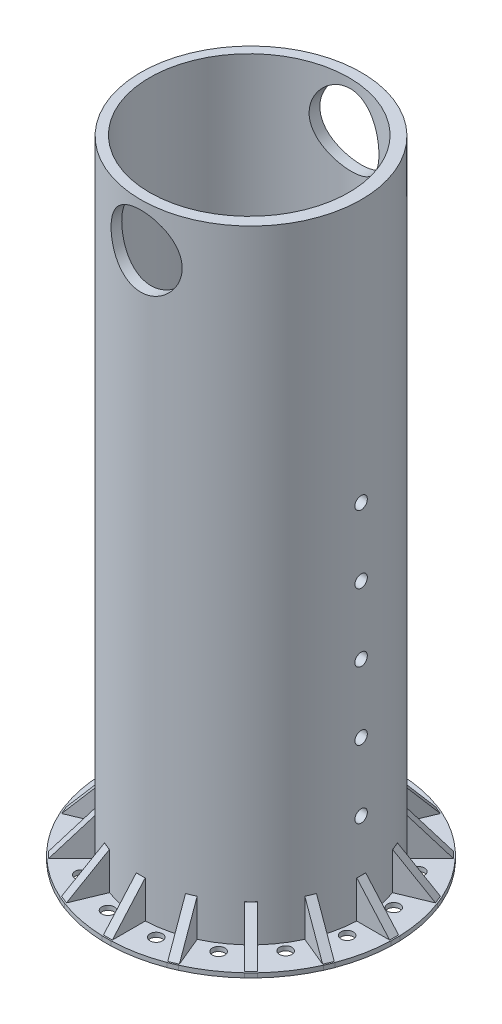
SolidWorks part; units mm, degrees
material "1023 Carbon Steel Sheet (SS)"
ref_plane "Front Plane" through (0, 0, 0) normal (0, 0, 1) x (1, 0, 0)
ref_plane "Top Plane" through (0, 0, 0) normal (0, 1, 0) x (1, 0, 0)
ref_plane "Right Plane" through (0, 0, 0) normal (1, 0, 0) x (0, 0, -1)
sketch "Sketch1" plane through (0, 0, 0) normal (0, 1, 0) x (1, 0, 0)
  circle A0 centre (0, 0) radius 162.5
  circle A1 centre (-1.9634, 0) radius 112
  dimension "D1" = 325
  dimension "D2" = 224
extrude "Boss-Extrude1" add sketch "Sketch1" along normal blind 5
sketch "Sketch2" plane through (0, 5, 0) normal (0, 1, 0) x (1, 0, 0)
  circle A0 centre (0, 0) radius 124
  circle A1 centre (-1.9634, 0) radius 112 construction
  circle A2 centre (-1.9634, 0) radius 112
  dimension "D1" = 248
extrude "Boss-Extrude2" add sketch "Sketch2" along normal blind 42
sketch "Sketch9" plane through (0, 47, 0) normal (0, 1, 0) x (1, 0, 0)
  line L1 (-119, 5) -> (-124, 5)
  line L2 (-119, 5) -> (-119, -5)
  line L3 (-119, -5) -> (-124, -5)
  line L4 (-124, 5) -> (-124, -5)
  circle A0 centre (0, 0) radius 124 construction
  circle A1 centre (0, 0) radius 124
  point P7 (-124, 0)
  circle M6 centre (0, 0) radius 124
  dimension "D1" = 10
  dimension "D2" = 5
extrude "Boss-Extrude7" add sketch "Sketch9" against normal blind 42 contours L3 L2 L1 M6
sketch "Sketch10" plane through (0, 0, 0) normal (0, 0, 1) x (1, 0, 0)
  line L0 (-124, 47) -> (-160.924, 5)
  line L1 (162.5, 5) -> (-162.5, 5) construction
  line L2 (-160.924, 5) -> (-124, 5)
  line L4 (-124, 5) -> (-124, 47)
sketch "Sketch11" plane through (0, 5, 0) normal (0, 1, 0) x (1, 0, 0)
  line L0 (-123.8992, -5) -> (-124, -5) construction
  line L1 (-124, 5) -> (-162.5, 5)
  line L2 (-124, 5) -> (-124, -5)
  line L3 (-124, -5) -> (-162.5, -5)
  line L4 (-162.5, 5) -> (-162.5, -5)
  circle A0 centre (0, 0) radius 162.5 construction
  circle A1 centre (0, 0) radius 162.5
  circle A3 centre (0, 0) radius 124 construction
  circle A4 centre (0, 0) radius 124
  point P8 (-162.5, 0)
  circle M6 centre (0, 0) radius 162.5
extrude "Boss-Extrude8" add sketch "Sketch11" against normal up to surface (5 mm away) contours L1 L4 M6 | L4 L3 L2 L1 M6
extrude "Boss-Extrude12" add sketch "Sketch10" along normal mid plane 10
pattern_circular "CirPattern1" count 16 over 360 about axis through (0, 0, 0) along (0, 1, 0) of "Boss-Extrude12", "Boss-Extrude8", "Boss-Extrude7"
sketch "Sketch13" plane through (0, 5, 0) normal (0, 1, 0) x (1, 0, 0)
  circle A0 centre (112.9258, -73.9781) radius 7
  circle A1 centre (0, 0) radius 135 construction
  dimension "D1" = 14
  dimension "D2" = 270
extrude "Cut-Extrude1" cut sketch "Sketch13" against normal through all
pattern_circular "CirPattern2" count 16 over 360 about axis through (-1.9634, 0, 0) along (0, 1, 0) of "Cut-Extrude1"
sketch "Sketch14" plane through (0, 47, 0) normal (0, 1, 0) x (1, 0, 0)
  circle A0 centre (0, 0) radius 124
  circle A2 centre (-1.9634, 0) radius 112 construction
  circle A3 centre (-1.9634, 0) radius 112
  dimension "D1" = 248
extrude "Boss-Extrude13" add sketch "Sketch14" along normal blind 658 contours A3 | A0
sketch "Sketch15" plane through (0, 0, 0) normal (0, 0, 1) x (1, 0, 0)
  line L0 (124, 705) -> (-124, 705) construction
  circle A0 centre (0, 655) radius 40
  dimension "D1" = 80
  dimension "D2" = 50
extrude "Cut-Extrude2" cut sketch "Sketch15" against normal through all both and the other way through all
sketch "Sketch16" plane through (0, 0, 0) normal (1, 0, 0) x (0, 0, -1)
  line L0 (42.7948, 5) -> (5, 5) construction
  line L1 (0, 705) -> (0, 0) construction
  line L2 (0, 0) -> (0, 253.6894) construction
  circle A0 centre (0, 105) radius 7
  circle A1 centre (0, 181.25) radius 7
  circle A2 centre (0, 257.5) radius 7
  circle A3 centre (0, 333.75) radius 7
  circle A4 centre (0, 410) radius 7
  point P4 (0, 337.4059)
  dimension "D1" = 14
  dimension "D2" = 100
  dimension "D4" = 305
  dimension "D3" = 5
extrude "Cut-Extrude3" cut sketch "Sketch16" against normal through all both and the other way through all
equation "\"d_o\"= 325"
equation "\"d_ii\"= 224"
equation "\"d_i\"= 238"
equation "\"D1@Sketch1\"=\"d_o\""
equation "\"D2@Sketch1\"=\"d_ii\""
equation "\"h\" = 700"
equation "\"D1@Boss-Extrude2\"=42"
equation "\"D1@Boss-Extrude13\"=\"h\"-42"
equation "\"D1@Sketch15\"=80"
